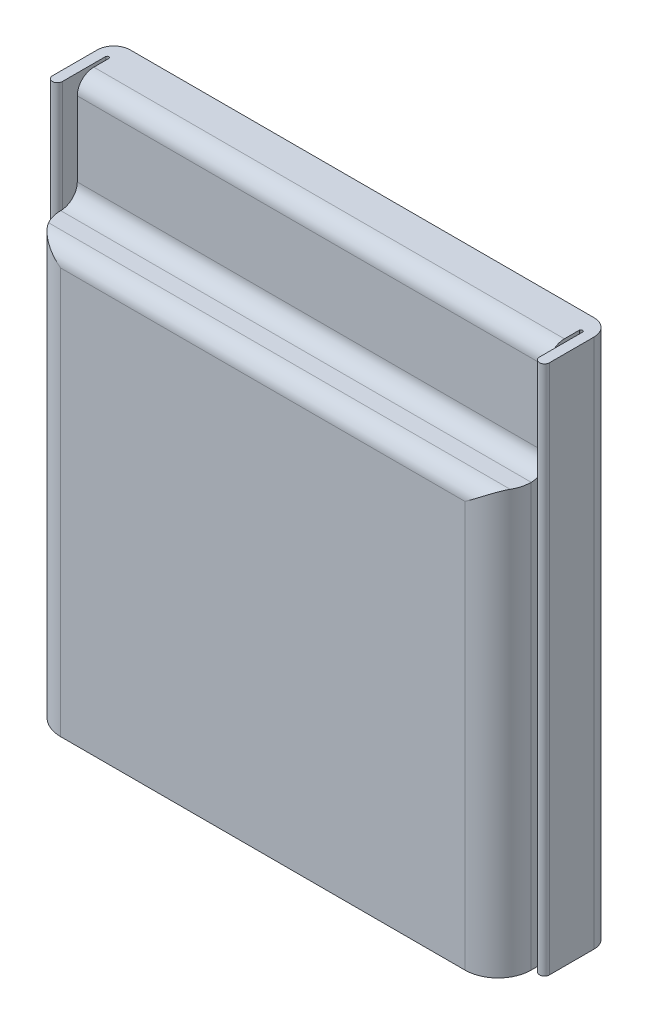
SolidWorks part; units mm, degrees
ref_plane "Front" through (0, 0, 0) normal (0, 0, 1) x (1, 0, 0)
ref_plane "Top" through (0, 0, 0) normal (0, 1, 0) x (1, 0, 0)
ref_plane "Right" through (0, 0, 0) normal (1, 0, 0) x (0, 0, -1)
sketch "Эскиз1" plane through (0, 0, 0) normal (0, 1, 0) x (1, 0, 0)
  line L0 (-14, 0) -> (14, 0)
  line L1 (-12.2, -6) -> (12.2, -6)
  line L2 (-15, -1) -> (-15, -3.7)
  line L3 (15, -1) -> (15, -3.7)
  line L4 (-14.2, -4) -> (-14.2, -1.1)
  line L5 (14.2, -1.1) -> (14.2, -4)
  line L6 (14.4, -3.7) -> (14.4, -1.1)
  line L7 (-14.4, -3.7) -> (-14.4, -1.1)
  arc A0 (-14, 0) -> (-15, -1) centre (-14, -1) ccw
  arc A1 (14, 0) -> (15, -1) centre (14, -1) cw
  arc A2 (-14.2, -4) -> (-12.2, -6) centre (-12.2, -4) ccw
  arc A3 (14.2, -4) -> (12.2, -6) centre (12.2, -4) cw
  arc A4 (15, -3.7) -> (14.4, -3.7) centre (14.7, -3.7) cw
  arc A5 (14.2, -1.1) -> (14.4, -1.1) centre (14.3, -1.1) cw
  arc A6 (-15, -3.7) -> (-14.4, -3.7) centre (-14.7, -3.7) ccw
  arc A7 (-14.2, -1.1) -> (-14.4, -1.1) centre (-14.3, -1.1) ccw
  point P20 (14.3, -1)
  point P21 (14.7, -4)
  point P27 (-14.3, -1)
  point P28 (-14.7, -4)
  dimension "D1" = 30
  dimension "D3" = 2
  dimension "D4" = 1
  dimension "D5" = 0.3
  dimension "D6" = 0.1
  dimension "D2" = 6
extrude "Бобышка-Вытянуть1" add sketch "Эскиз1" along normal mid plane 32
sketch "Эскиз2" plane through (0, 0, 0) normal (1, 0, 0) x (0, 0, -1)
  line L0 (-3, 15) -> (-3, 10.5)
  line L1 (-4, 9.5) -> (-5, 9.5)
  line L2 (-6, 16) -> (-6, 8.5)
  line L3 (-6, 16) -> (-6, -16) construction
  line L6 (-6, 16) -> (-2, 16)
  line L7 (0, 16) -> (-1, 16) construction
  arc A0 (-3, 10.5) -> (-4, 9.5) centre (-4, 10.5) cw
  arc A1 (-5, 9.5) -> (-6, 8.5) centre (-5, 8.5) ccw
  arc A2 (-2, 16) -> (-3, 15) centre (-2, 15) ccw
  dimension "D1" = 1
  dimension "D2" = 3
  dimension "D3" = 6.5
extrude "Вырез-Вытянуть1" cut sketch "Эскиз2" against normal up to next and the other way up to next
